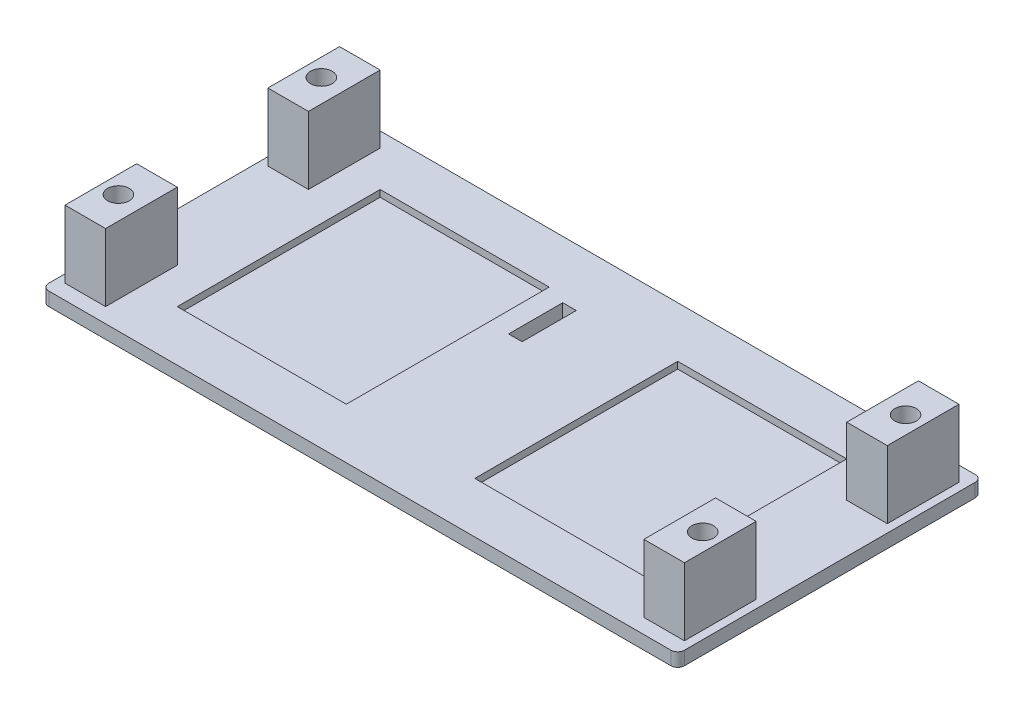
SolidWorks part; units mm, degrees
ref_plane "Front Plane" through (0, 0, 0) normal (0, 0, 1) x (1, 0, 0)
ref_plane "Top Plane" through (0, 0, 0) normal (0, 1, 0) x (1, 0, 0)
ref_plane "Right Plane" through (0, 0, 0) normal (1, 0, 0) x (0, 0, -1)
sketch "Sketch1" plane through (0, 0, 0) normal (0, 1, 0) x (1, 0, 0)
  line L1 (-47, -22.5) -> (47, -22.5)
  line L2 (-47, -22.5) -> (-47, 22.5)
  line L3 (-47, 22.5) -> (47, 22.5)
  line L4 (47, -22.5) -> (47, 22.5)
  line L5 (-47, -22.5) -> (47, 22.5) construction
  line L6 (-47, 22.5) -> (47, -22.5) construction
  point P0 (0, 0)
  dimension "D1" = 45
  dimension "D2" = 94
extrude "Boss-Extrude1" add sketch "Sketch1" along normal blind 2
fillet "Fillet1" radius 1
sketch "Sketch2" plane through (0, 2, 0) normal (0, 1, 0) x (1, 0, 0)
  line L0 (-47, 21.5) -> (-47, -21.5) construction
  line L1 (-39.8, -20.3) -> (-45.8, -20.3)
  line L2 (-39.8, -20.3) -> (-39.8, -9.7)
  line L3 (-39.8, -9.7) -> (-45.8, -9.7)
  line L4 (-45.8, -20.3) -> (-45.8, -9.7)
  line L5 (-39.8, -20.3) -> (-45.8, -9.7) construction
  line L6 (-39.8, -9.7) -> (-45.8, -20.3) construction
  line L7 (-39.8, 20.3) -> (-45.8, 20.3)
  line L8 (-39.8, 20.3) -> (-39.8, 9.7)
  line L9 (-39.8, 9.7) -> (-45.8, 9.7)
  line L10 (-45.8, 20.3) -> (-45.8, 9.7)
  line L11 (-39.8, 20.3) -> (-45.8, 9.7) construction
  line L12 (-39.8, 9.7) -> (-45.8, 20.3) construction
  line L13 (46, 22.5) -> (-46, 22.5) construction
  line L14 (-46, -22.5) -> (46, -22.5) construction
  point P0 (-42.8, -15)
  point P5 (-42.8, 15)
  dimension "D1" = 1.2
  dimension "D2" = 2.2
  dimension "D3" = 2.2
  dimension "D4" = 1.2
  dimension "D5" = 10.6
  dimension "D6" = 10.6
  dimension "D7" = 6
  dimension "D8" = 6
extrude "Boss-Extrude2" add sketch "Sketch2" along normal blind 10
ref_plane "Plane1" through (0, 0, 0) normal (-1, 0, 0) x (0, 0, 1)
sketch "Sketch5" plane through (0, 0, 0) normal (0, -1, 0) x (1, 0, 0)
  line L0 (-45.8, 9.7) -> (-45.8, 20.3) construction
  line L1 (-45.8, -20.3) -> (-45.8, -9.7) construction
  line L2 (-45.8, 9.7) -> (-45.8, 20.3) construction
  line L3 (-45.8, -20.3) -> (-45.8, -9.7) construction
  line L4 (-45.8, -15) -> (-43.2, -15) construction
  line L5 (-45.8, 15) -> (-43.2, 15) construction
  point P9 (-43.2, 15)
  point P10 (-43.2, -15)
  dimension "D1" = 2.6
  dimension "D2" = 2.6
sketch "Sketch8" plane through (0, 2, 0) normal (0, 1, 0) x (1, 0, 0)
  line L0 (47, -21.5) -> (47, 21.5) construction
  line L1 (-34.5, -15) -> (-9.5, -15)
  line L2 (-34.5, -15) -> (-34.5, 15)
  line L3 (-34.5, 15) -> (-9.5, 15)
  line L4 (-9.5, -15) -> (-9.5, 15)
  line L5 (-34.5, -15) -> (-9.5, 15) construction
  line L6 (-34.5, 15) -> (-9.5, -15) construction
  line L8 (47, 0) -> (-47, 0) construction
  line L9 (-47, 21.5) -> (-47, -21.5) construction
  point P0 (-22, 0)
  dimension "D1" = 25
  dimension "D2" = 30
  dimension "D3" = 25
extrude "Cut-Extrude1" cut sketch "Sketch8" against normal blind 1
hole_wizard "CSK for M5 Countersunk Flat Head Screw1" positions "3DSketch3" profile "Sketch7" countersink size "M5" standard "DIN"
sketch3d "3DSketch3"
  point P0 (-43.2, 0, -15)
  point P3 (-43.2, 0, 15)
sketch "Sketch7" plane through (-43.2, 0, -15) normal (1, 0, 0) x (0, 0, -1)
  line L0 (0, 0) -> (0, 15)
  line L1 (0, 15) -> (1.6, 15)
  line L2 (1.6, 15) -> (1.6, 1.4)
  line L3 (1.6, 1.4) -> (3, 0)
  line L5 (3, 0) -> (0, 0)
  line L6 (-1.6, 1.4) -> (-3, 0) construction
  line L10 (0, 15) -> (-1.6, 15) construction
  line L11 (0, -6.35) -> (0, 107.95) construction
  dimension "Hole Dia." = 3.2
  dimension "Hole Depth" = 15
  dimension "Near C'Sink Dia." = 6
  dimension "Near C'Sink Angle" = 90
  dimension "Drill Angle" = 180
mirror "Mirror1" about plane through (0, 0, 0) normal (-1, 0, 0) of "Cut-Extrude1", "Boss-Extrude2", "CSK for M5 Countersunk Flat Head Screw1"
sketch "Sketch9" plane through (0, 0, 0) normal (0, -1, 0) x (1, 0, 0)
  line L0 (46, -22.5) -> (-46, -22.5) construction
  line L1 (-4.5, -14) -> (-6.5, -14)
  line L2 (-4.5, -14) -> (-4.5, -6)
  line L3 (-4.5, -6) -> (-6.5, -6)
  line L4 (-6.5, -14) -> (-6.5, -6)
  line L5 (-47, -21.5) -> (-47, 21.5) construction
  dimension "D1" = 2
  dimension "D2" = 8
  dimension "D3" = 8.5
  dimension "D4" = 40.5
extrude "Cut-Extrude2" cut sketch "Sketch9" against normal up to next
